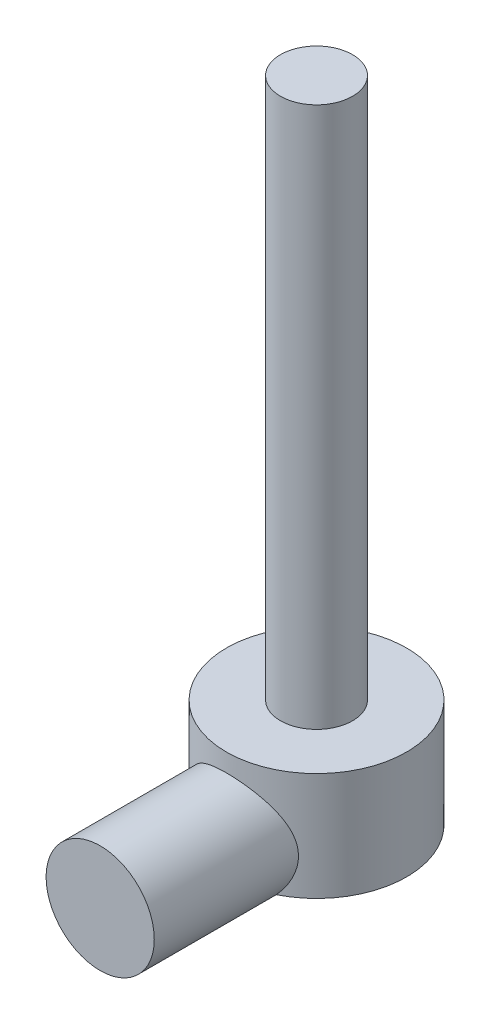
SolidWorks part; units mm, degrees
ref_plane "Front Plane" through (0, 0, 0) normal (0, 0, 1) x (1, 0, 0)
ref_plane "Top Plane" through (0, 0, 0) normal (0, 1, 0) x (1, 0, 0)
ref_plane "Right Plane" through (0, 0, 0) normal (1, 0, 0) x (0, 0, -1)
sketch "Sketch1" plane through (0, 0, 0) normal (0, 0, 1) x (1, 0, 0)
  circle A0 centre (0, 0) radius 30
  dimension "D1" = 60
extrude "Boss-Extrude1" add sketch "Sketch1" along normal blind 120
sketch "Sketch2" plane through (0, 0, 0) normal (0, 0, 1) x (1, 0, 0)
  line L0 (30, 0) -> (-30, 0) construction
  circle A0 centre (0, 0) radius 30 construction
ref_plane "Plane1" through (0, 0, 0) normal (0, 1, 0) x (-1, 0, 0)
sketch "Sketch3" plane through (0, 0, 0) normal (0, 1, 0) x (-1, 0, 0)
  circle A0 centre (0, 0) radius 50
  dimension "D1" = 100
extrude "Boss-Extrude2" add sketch "Sketch3" along normal blind 40 and the other way blind 20
sketch "Sketch4" plane through (0, 40, 0) normal (0, 1, 0) x (1, 0, 0)
  circle A0 centre (0, 0) radius 20
  dimension "D1" = 40
extrude "Boss-Extrude3" add sketch "Sketch4" along normal blind 300
